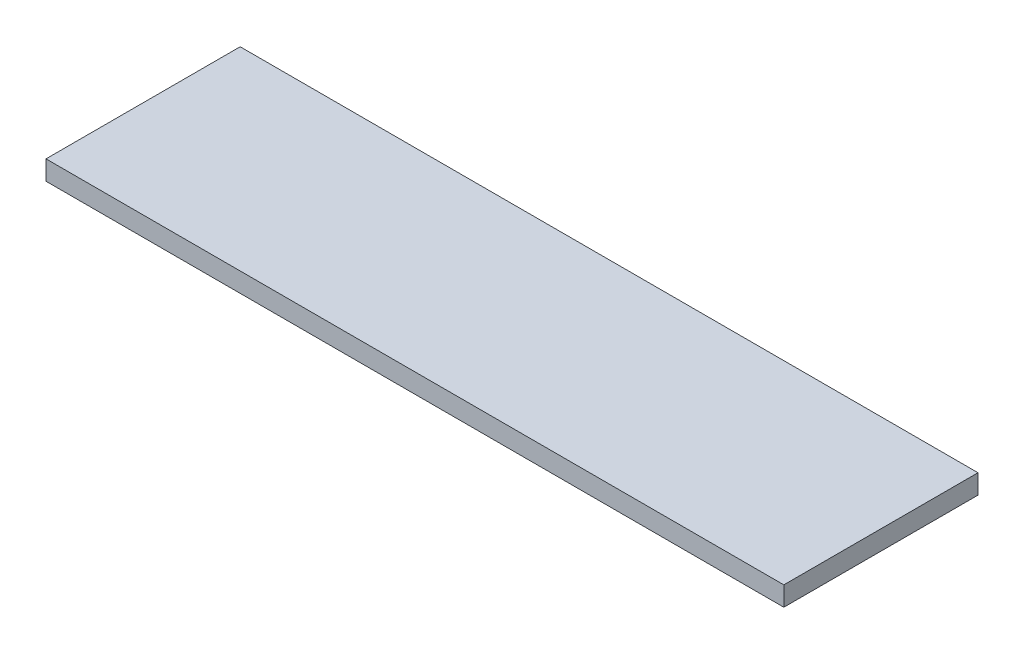
SolidWorks part; units mm, degrees
ref_plane "Front Plane" through (0, 0, 0) normal (0, 0, 1) x (1, 0, 0)
ref_plane "Top Plane" through (0, 0, 0) normal (0, 1, 0) x (1, 0, 0)
ref_plane "Right Plane" through (0, 0, 0) normal (1, 0, 0) x (0, 0, -1)
sketch "Sketch1" plane through (0, 0, 0) normal (0, 1, 0) x (1, 0, 0)
  line L1 (0, 0) -> (120.65, 0)
  line L2 (0, 0) -> (0, 31.75)
  line L3 (0, 31.75) -> (120.65, 31.75)
  line L4 (120.65, 0) -> (120.65, 31.75)
  dimension "D1" = 120.65
  dimension "D2" = 31.75
extrude "Boss-Extrude1" add sketch "Sketch1" along normal blind 3.175
